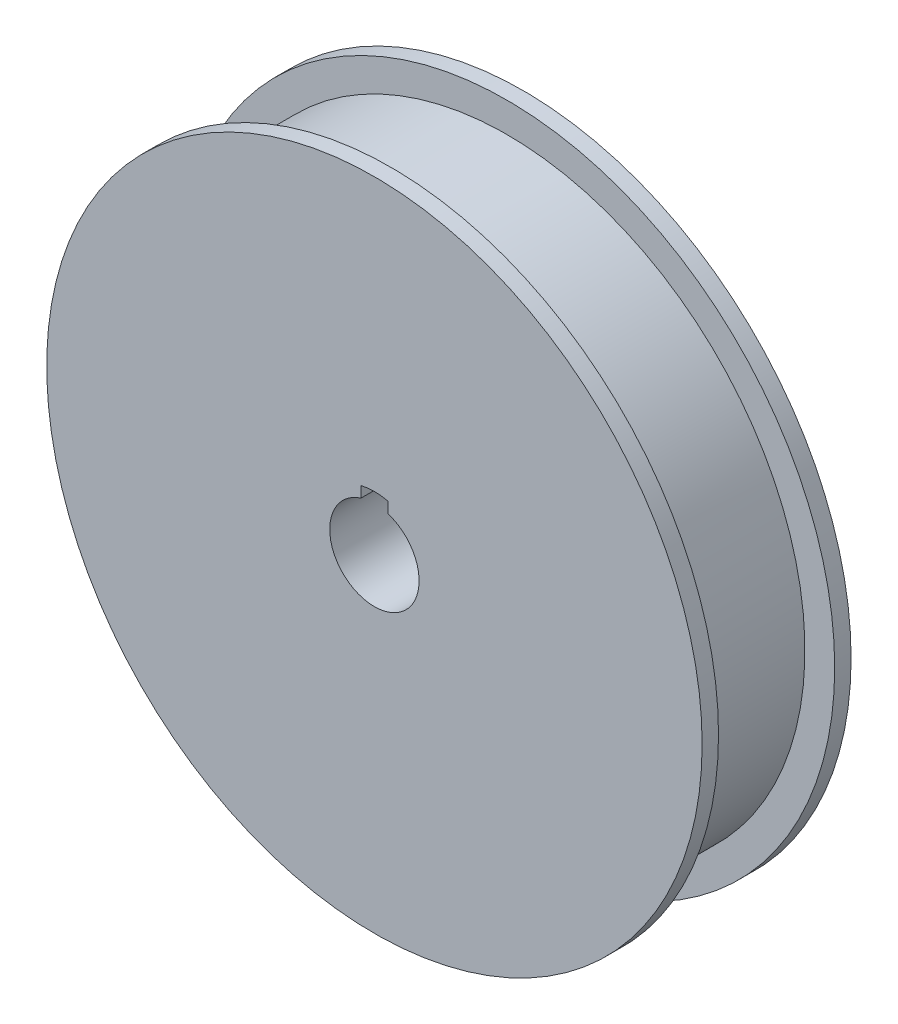
SolidWorks part; units mm, degrees
ref_plane "Front Plane" through (0, 0, 0) normal (0, 0, 1) x (1, 0, 0)
ref_plane "Top Plane" through (0, 0, 0) normal (0, 1, 0) x (1, 0, 0)
ref_plane "Right Plane" through (0, 0, 0) normal (1, 0, 0) x (0, 0, -1)
sketch "Sketch1" plane through (0, 0, 0) normal (0, 0, 1) x (1, 0, 0)
  circle A0 centre (0, 0) radius 200
  circle A1 centre (0, 0) radius 30
  dimension "D1" = 400
  dimension "D2" = 60
extrude "Boss-Extrude1" add sketch "Sketch1" along normal mid plane 100
sketch "Sketch2" plane through (0, 0, 50) normal (0, 0, 1) x (1, 0, 0)
  circle A0 centre (0, 0) radius 30 construction
  circle A1 centre (0, 0) radius 30
  circle A4 centre (0, 0) radius 220
  circle A5 centre (0, 0) radius 220
  dimension "D1" = 20
extrude "Boss-Extrude2" add sketch "Sketch2" against normal blind 11
mirror "Mirror1" about plane through (0, 0, 0) normal (0, 0, 1) of "Boss-Extrude2"
sketch "Sketch3" plane through (0, 0, 50) normal (0, 0, 1) x (1, 0, 0)
  line L0 (0, 0) -> (0, 37) construction
  line L1 (9, 19.4566) -> (9, 35.8887)
  line L2 (-9, 19.4566) -> (-9, 35.8887)
  line L3 (-9, 19.4566) -> (9, 19.4566)
  line L4 (-9, 0) -> (-9, 108.3079) construction
  line L5 (0, 0) -> (0, 108.3079) construction
  line L6 (9, 0) -> (9, 108.3079) construction
  circle A2 centre (0, 0) radius 37
  arc A3 (9, 35.8887) -> (-9, 35.8887) centre (0, 0) ccw
  dimension "D4" = 19.4566
  dimension "D1" = 9
  dimension "D2" = 9
  dimension "D3" = 7
extrude "Cut-Extrude1" cut sketch "Sketch3" against normal through all
